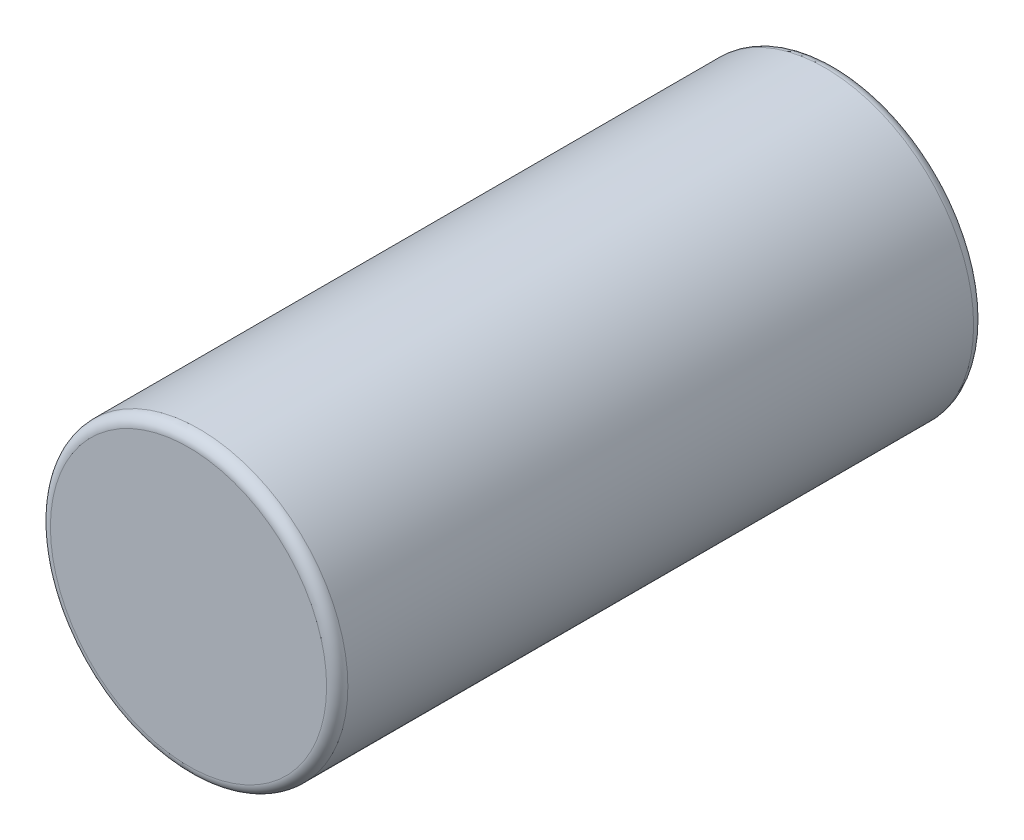
SolidWorks part; units mm, degrees
ref_plane "Front Plane" through (0, 0, 0) normal (0, 0, 1) x (1, 0, 0)
ref_plane "Top Plane" through (0, 0, 0) normal (0, 1, 0) x (1, 0, 0)
ref_plane "Right Plane" through (0, 0, 0) normal (1, 0, 0) x (0, 0, -1)
sketch "Sketch1" plane through (0, 0, 0) normal (1, 0, 0) x (0, 0, -1)
  line L0 (0, 0) -> (35.9757, 0) construction
  line L1 (0, 0) -> (0, 6.5)
  line L2 (0.5, 7) -> (29.95, 7)
  line L3 (30.45, 6.5) -> (30.45, 0)
  line L4 (0, 0) -> (30.45, 0)
  arc A0 (29.95, 7) -> (30.45, 6.5) centre (29.95, 6.5) cw
  arc A1 (0, 6.5) -> (0.5, 7) centre (0.5, 6.5) cw
  dimension "D3" = 0.5
  dimension "D1" = 14
  dimension "D2" = 30.45
revolve "Revolve1" add sketch "Sketch1" angle 360 about L0
